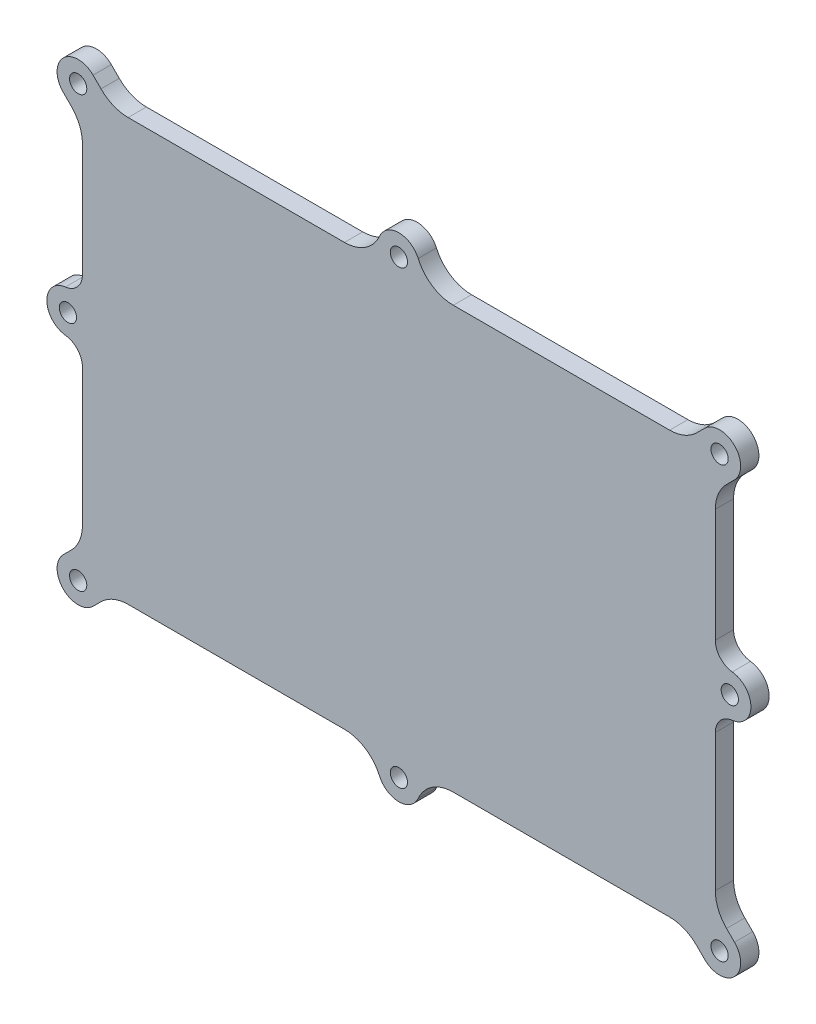
SolidWorks part; units mm, degrees
material "Custom Plastic"
ref_plane "X-Y Datum" through (0, 0, 0) normal (0, 0, 1) x (1, 0, 0)
ref_plane "X-Z Datum" through (0, 0, 0) normal (0, 1, 0) x (1, 0, 0)
ref_plane "Y-Z Datum" through (0, 0, 0) normal (1, 0, 0) x (0, 0, -1)
sketch "Sketch2" plane through (0, 0, 0) normal (0, 0, 1) x (1, 0, 0)
  line L16 (183.5533, 104.3328) -> (181.4806, 102.2601)
  line L17 (174.4096, 99.3312) -> (117.9783, 99.3312)
  line L18 (89.5814, 99.3312) -> (33.1502, 99.3312)
  line L19 (26.0791, 102.2601) -> (24.0065, 104.3328)
  line L20 (16.2283, 96.5546) -> (18.3009, 94.4819)
  line L21 (21.2299, 87.4109) -> (21.2299, 57.8401)
  line L22 (21.2299, 36.9817) -> (21.2299, 1.2515)
  line L23 (18.3009, -5.8196) -> (16.2283, -7.8922)
  line L24 (24.0065, -15.6704) -> (26.0791, -13.5977)
  line L25 (33.1502, -10.6688) -> (89.5814, -10.6688)
  line L26 (117.9783, -10.6688) -> (174.4096, -10.6688)
  line L27 (181.4806, -13.5977) -> (183.5533, -15.6704)
  line L28 (191.3314, -7.8922) -> (189.2588, -5.8196)
  line L29 (186.3299, 1.2515) -> (186.3299, 36.9817)
  line L30 (186.3299, 57.8401) -> (186.3299, 87.4109)
  line L31 (189.2588, 94.4819) -> (191.3314, 96.5546)
  line L32 (183.5533, 104.3328) -> (181.4806, 102.2601)
  line L33 (174.4096, 99.3312) -> (117.9783, 99.3312)
  line L34 (89.5814, 99.3312) -> (33.1502, 99.3312)
  line L35 (26.0791, 102.2601) -> (24.0065, 104.3328)
  line L36 (16.2283, 96.5546) -> (18.3009, 94.4819)
  line L37 (21.2299, 87.4109) -> (21.2299, 57.8401)
  line L38 (21.2299, 36.9817) -> (21.2299, 1.2515)
  line L39 (18.3009, -5.8196) -> (16.2283, -7.8922)
  line L40 (24.0065, -15.6704) -> (26.0791, -13.5977)
  line L41 (33.1502, -10.6688) -> (89.5814, -10.6688)
  line L42 (117.9783, -10.6688) -> (174.4096, -10.6688)
  line L43 (181.4806, -13.5977) -> (183.5533, -15.6704)
  line L44 (191.3314, -7.8922) -> (189.2588, -5.8196)
  line L45 (186.3299, 1.2515) -> (186.3299, 36.9817)
  line L46 (186.3299, 57.8401) -> (186.3299, 87.4109)
  line L47 (189.2588, 94.4819) -> (191.3314, 96.5546)
  arc A24 (174.4096, 99.3312) -> (181.4806, 102.2601) centre (174.4096, 109.3312) ccw
  arc A25 (108.818, 105.32) -> (117.9783, 99.3312) centre (117.9783, 109.3312) ccw
  arc A26 (108.818, 105.32) -> (98.7417, 105.32) centre (103.7799, 103.1139) ccw
  arc A27 (89.5814, 99.3312) -> (98.7417, 105.32) centre (89.5814, 109.3312) ccw
  arc A28 (26.0791, 102.2601) -> (33.1502, 99.3312) centre (33.1502, 109.3312) ccw
  arc A29 (24.0065, 104.3328) -> (16.2283, 96.5546) centre (20.1174, 100.4437) ccw
  arc A30 (21.2299, 87.4109) -> (18.3009, 94.4819) centre (11.2299, 87.4109) ccw
  arc A31 (16.8095, 52.8738) -> (21.2299, 57.8401) centre (16.2299, 57.8401) ccw
  arc A32 (16.8095, 52.8738) -> (16.8095, 41.948) centre (17.4472, 47.4109) ccw
  arc A33 (21.2299, 36.9817) -> (16.8095, 41.948) centre (16.2299, 36.9817) ccw
  arc A34 (18.3009, -5.8196) -> (21.2299, 1.2515) centre (11.2299, 1.2515) ccw
  arc A35 (16.2283, -7.8922) -> (24.0065, -15.6704) centre (20.1174, -11.7813) ccw
  arc A36 (33.1502, -10.6688) -> (26.0791, -13.5977) centre (33.1502, -20.6688) ccw
  arc A37 (98.7417, -16.6577) -> (89.5814, -10.6688) centre (89.5814, -20.6688) ccw
  arc A38 (98.7417, -16.6577) -> (108.818, -16.6577) centre (103.7799, -14.4515) ccw
  arc A39 (117.9783, -10.6688) -> (108.818, -16.6577) centre (117.9783, -20.6688) ccw
  arc A40 (181.4806, -13.5977) -> (174.4096, -10.6688) centre (174.4096, -20.6688) ccw
  arc A41 (183.5533, -15.6704) -> (191.3314, -7.8922) centre (187.4423, -11.7813) ccw
  arc A42 (186.3299, 1.2515) -> (189.2588, -5.8196) centre (196.3299, 1.2515) ccw
  arc A43 (190.7502, 41.948) -> (186.3299, 36.9817) centre (191.3299, 36.9817) ccw
  arc A44 (190.7502, 41.948) -> (190.7502, 52.8738) centre (190.1126, 47.4109) ccw
  arc A45 (186.3299, 57.8401) -> (190.7502, 52.8738) centre (191.3299, 57.8401) ccw
  arc A46 (189.2588, 94.4819) -> (186.3299, 87.4109) centre (196.3299, 87.4109) ccw
  arc A47 (191.3314, 96.5546) -> (183.5533, 104.3328) centre (187.4423, 100.4437) ccw
  arc A48 (174.4096, 99.3312) -> (181.4806, 102.2601) centre (174.4096, 109.3312) ccw
  arc A49 (108.818, 105.32) -> (117.9783, 99.3312) centre (117.9783, 109.3312) ccw
  arc A50 (108.818, 105.32) -> (98.7417, 105.32) centre (103.7799, 103.1139) ccw
  arc A51 (89.5814, 99.3312) -> (98.7417, 105.32) centre (89.5814, 109.3312) ccw
  arc A52 (26.0791, 102.2601) -> (33.1502, 99.3312) centre (33.1502, 109.3312) ccw
  arc A53 (24.0065, 104.3328) -> (16.2283, 96.5546) centre (20.1174, 100.4437) ccw
  arc A54 (21.2299, 87.4109) -> (18.3009, 94.4819) centre (11.2299, 87.4109) ccw
  arc A55 (16.8095, 52.8738) -> (21.2299, 57.8401) centre (16.2299, 57.8401) ccw
  arc A56 (16.8095, 52.8738) -> (16.8095, 41.948) centre (17.4472, 47.4109) ccw
  arc A57 (21.2299, 36.9817) -> (16.8095, 41.948) centre (16.2299, 36.9817) ccw
  arc A58 (18.3009, -5.8196) -> (21.2299, 1.2515) centre (11.2299, 1.2515) ccw
  arc A59 (16.2283, -7.8922) -> (24.0065, -15.6704) centre (20.1174, -11.7813) ccw
  arc A60 (33.1502, -10.6688) -> (26.0791, -13.5977) centre (33.1502, -20.6688) ccw
  arc A61 (98.7417, -16.6577) -> (89.5814, -10.6688) centre (89.5814, -20.6688) ccw
  arc A62 (98.7417, -16.6577) -> (108.818, -16.6577) centre (103.7799, -14.4515) ccw
  arc A63 (117.9783, -10.6688) -> (108.818, -16.6577) centre (117.9783, -20.6688) ccw
  arc A64 (181.4806, -13.5977) -> (174.4096, -10.6688) centre (174.4096, -20.6688) ccw
  arc A65 (183.5533, -15.6704) -> (191.3314, -7.8922) centre (187.4423, -11.7813) ccw
  arc A66 (186.3299, 1.2515) -> (189.2588, -5.8196) centre (196.3299, 1.2515) ccw
  arc A67 (190.7502, 41.948) -> (186.3299, 36.9817) centre (191.3299, 36.9817) ccw
  arc A68 (190.7502, 41.948) -> (190.7502, 52.8738) centre (190.1126, 47.4109) ccw
  arc A69 (186.3299, 57.8401) -> (190.7502, 52.8738) centre (191.3299, 57.8401) ccw
  arc A70 (189.2588, 94.4819) -> (186.3299, 87.4109) centre (196.3299, 87.4109) ccw
  arc A71 (191.3314, 96.5546) -> (183.5533, 104.3328) centre (187.4423, 100.4437) ccw
  dimension "D1" = 0
extrude "Boss-Extrude1" add sketch "Sketch2" along normal blind 4.7625
sketch "Sketch5" plane through (0, 0, 4.7625) normal (0, 0, 1) x (1, 0, 0)
  point P0 (17.4472, 47.4109)
  point P1 (20.1174, 100.4437)
  point P3 (103.7799, 103.1139)
  point P5 (187.4423, 100.4437)
  point P7 (190.1126, 47.4109)
  point P9 (187.4423, -11.7813)
  point P11 (103.7799, -14.4515)
  point P13 (20.1174, -11.7813)
hole_wizard "M4 Clearance Hole1" positions "Sketch5" profile "Sketch6" hole size "M4" standard "ANSI Metric" end condition through all
sketch "Sketch6" plane through (17.4472, 47.4109, 4.7625) normal (1, 0, 0) x (0, -1, 0)
  line L0 (0, 0) -> (0, 4.7625)
  line L1 (0, 4.7625) -> (2.25, 4.7625)
  line L2 (2.25, 4.7625) -> (2.25, 0)
  line L5 (2.25, 0) -> (0, 0)
  line L11 (0, -6.35) -> (0, 107.95) construction
  dimension "Thru Hole Dia." = 4.5
  dimension "Thru Hole Depth" = 4.7625
